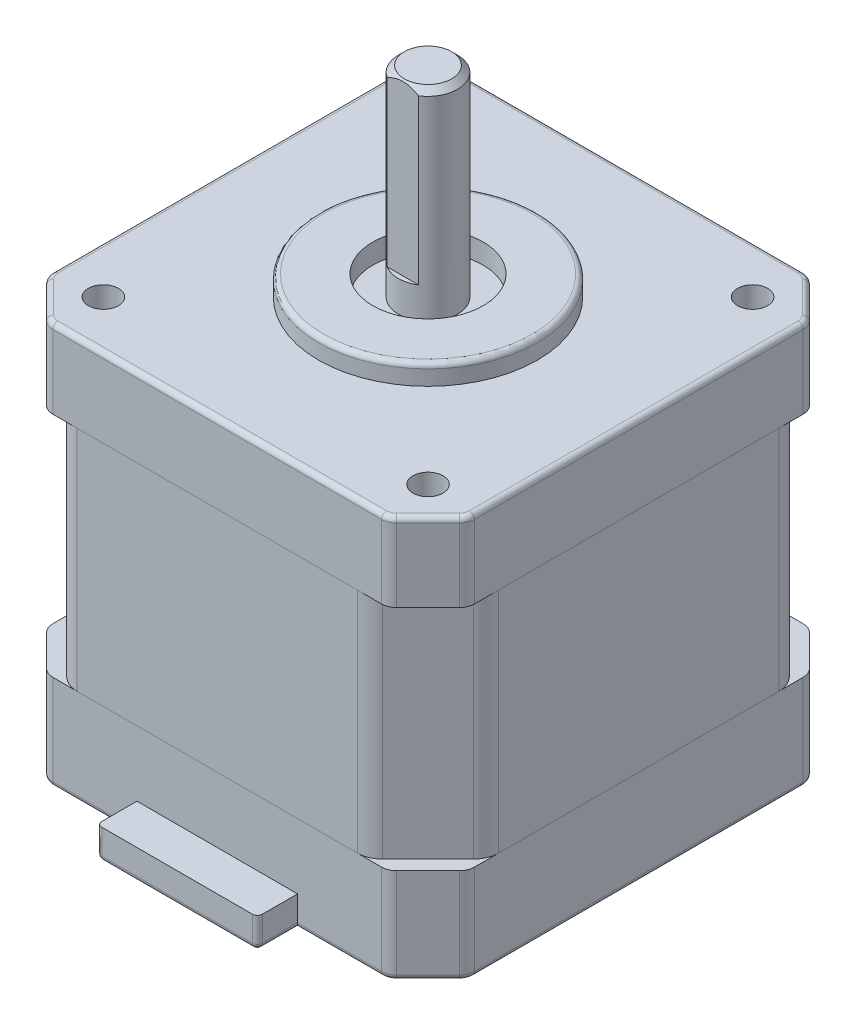
SolidWorks part; units mm, degrees
ref_plane "Front Plane" through (0, 0, 0) normal (0, 0, 1) x (1, 0, 0)
ref_plane "Top Plane" through (0, 0, 0) normal (0, 1, 0) x (1, 0, 0)
ref_plane "Right Plane" through (0, 0, 0) normal (1, 0, 0) x (0, 0, -1)
sketch "Sketch1" plane through (0, 0, 0) normal (0, 1, 0) x (1, 0, 0)
  line L1 (-21, 21) -> (21, 21)
  line L2 (-21, 21) -> (-21, -21)
  line L3 (-21, -21) -> (21, -21)
  line L4 (21, 21) -> (21, -21)
  line L5 (-21, 21) -> (21, -21) construction
  line L6 (-21, -21) -> (21, 21) construction
  point P0 (0, 0)
  dimension "D1" = 42
  dimension "D2" = 42
extrude "Boss-Extrude1" add sketch "Sketch1" along normal blind 40
sketch "Sketch3" plane through (0, 40, 0) normal (0, 1, 0) x (1, 0, 0)
  circle A0 centre (0, 0) radius 10.9
  circle A1 centre (0, 0) radius 5.5
  dimension "D1" = 21.8
  dimension "D2" = 11
extrude "Boss-Extrude2" add sketch "Sketch3" along normal blind 2
sketch "Sketch4" plane through (0, 40, 0) normal (0, 1, 0) x (1, 0, 0)
  circle A0 centre (0, 0) radius 2.95
  dimension "D1" = 5.9
extrude "Boss-Extrude3" add sketch "Sketch4" along normal blind 20
ref_plane "Plane1" through (0, 9.5, 0) normal (0, -1, 0) x (-1, 0, 0)
split "Split1" trim tools "Plane1" bodies to split 103 resulting bodies 104 105
ref_plane "Plane2" through (0, 32.2, 0) normal (0, 1, 0) x (1, 0, 0)
split "Split2" trim tools "Plane2" bodies to split 105 resulting bodies 106 107
chamfer "Chamfer1" distance 6 angle 45 4 edges at (-21, 20.85, 21) (-21, 20.85, -21) (21, 20.85, -21) (21, 20.85, 21)
chamfer "Chamfer2" distance 4 angle 45 4 edges at (21, 36.1, 21) (-21, 36.1, 21) (-21, 36.1, -21) (21, 36.1, -21)
chamfer "Chamfer3" distance 4 angle 45 4 edges at (21, 4.75, -21) (21, 4.75, 21) (-21, 4.75, 21) (-21, 4.75, -21)
fillet "Fillet1" radius 2.5 8 edges at (-15, 20.85, 21) (-21, 20.85, 15) (-21, 20.85, -15) (-15, 20.85, -21) (15, 20.85, -21) (21, 20.85, -15) (15, 20.85, 21) (21, 20.85, 15)
fillet "Fillet2" radius 1.5 8 edges at (17, 4.75, -21) (21, 4.75, -17) (21, 4.75, 17) (17, 4.75, 21) (-17, 4.75, 21) (-21, 4.75, 17) (-17, 4.75, -21) (-21, 4.75, -17)
fillet "Fillet3" radius 1.5 8 edges at (-17, 36.1, -21) (17, 36.1, -21) (21, 36.1, -17) (21, 36.1, 17) (17, 36.1, 21) (-17, 36.1, 21) (-21, 36.1, 17) (-21, 36.1, -17)
chamfer "Chamfer4" distance 0.6 angle 45 1 edges at (0, 60, 2.95)
sketch "Sketch5" plane through (0, 0, 21) normal (0, 0, 1) x (1, 0, 0)
  line L0 (-16.3787, 0) -> (16.3787, 0) construction
  line L1 (-8, 3) -> (8, 3)
  line L2 (-8, 3) -> (-8, 0)
  line L3 (-8, 0) -> (8, 0)
  line L4 (8, 3) -> (8, 0)
  point P6 (0, 0)
  dimension "D1" = 16
  dimension "D2" = 3
extrude "Boss-Extrude4" add sketch "Sketch5" along normal blind 4
sketch "Sketch6" plane through (0, 0, 0) normal (0, -1, 0) x (1, 0, 0)
  circle A0 centre (0, 0) radius 4.5
  dimension "D1" = 9
extrude "Cut-Extrude1" cut sketch "Sketch6" against normal blind 4
sketch "Sketch7" plane through (0, 40, 0) normal (0, 1, 0) x (1, 0, 0)
  line L0 (-19, 19) -> (0, 0) construction
  line L1 (-17.4393, 20.5607) -> (-20.5607, 17.4393) construction
  circle A0 centre (-16.1716, 16.1716) radius 1.5
  circle A1 centre (16.1716, 16.1716) radius 1.5
  circle A2 centre (16.1716, -16.1716) radius 1.5
  circle A3 centre (-16.1716, -16.1716) radius 1.5
  point P16 (0, 0)
  dimension "D2" = 3
  dimension "D1" = 4
  dimension "D3" = 4
extrude "Cut-Extrude2" cut sketch "Sketch7" against normal blind 7.5
fillet "Fillet4" radius 0.5 16 edges at (-20.8858, 40, -16.9527) (-19, 40, -19) (-16.9527, 40, -20.8858) (0, 40, -21) (16.9527, 40, -20.8858) (19, 40, -19) (20.8858, 40, -16.9527) (21, 40, 0) (20.8858, 40, 16.9527) (19, 40, 19) (16.9527, 40, 20.8858) (0, 40, 21) (-16.9527, 40, 20.8858) (-19, 40, 19) (-20.8858, 40, 16.9527) (-21, 40, 0)
fillet "Fillet5" radius 0.5 1 edges at (0, 42, 10.9)
fillet "Fillet6" radius 0.5 23 edges at (0, 0, -4.5) (8, 1.5, 25) (-8, 1.5, 25) (-16.9527, 0, -20.8858) (-19, 0, -19) (-20.8858, 0, -16.9527) (-21, 0, 0) (-20.8858, 0, 16.9527) (-19, 0, 19) (-16.9527, 0, 20.8858) (-12.1893, 0, 21) (-8, 0, 23) (0, 0, 25) (8, 0, 23) (12.1893, 0, 21) (16.9527, 0, 20.8858) (19, 0, 19) (20.8858, 0, 16.9527) (21, 0, 0) (20.8858, 0, -16.9527) (19, 0, -19) (16.9527, 0, -20.8858) (0, 0, -21)
ref_plane "Plane3" through (0, 0, 2.5) normal (0, 0, 1) x (1, 0, 0)
sketch "Sketch8" plane through (0, 0, 2.5) normal (0, 0, 1) x (1, 0, 0)
  line L1 (-13.9152, 78.4916) -> (4.2935, 78.4916)
  line L2 (-13.9152, 78.4916) -> (-13.9152, 43.0707)
  line L3 (-13.9152, 43.0707) -> (4.2935, 43.0707)
  line L4 (4.2935, 78.4916) -> (4.2935, 43.0707)
  line L5 (-13.9152, 78.4916) -> (4.2935, 43.0707) construction
  line L6 (-13.9152, 43.0707) -> (4.2935, 78.4916) construction
  point P0 (-4.8108, 60.7812)
extrude "Cut-Extrude4" cut sketch "Sketch8" along normal blind 6
